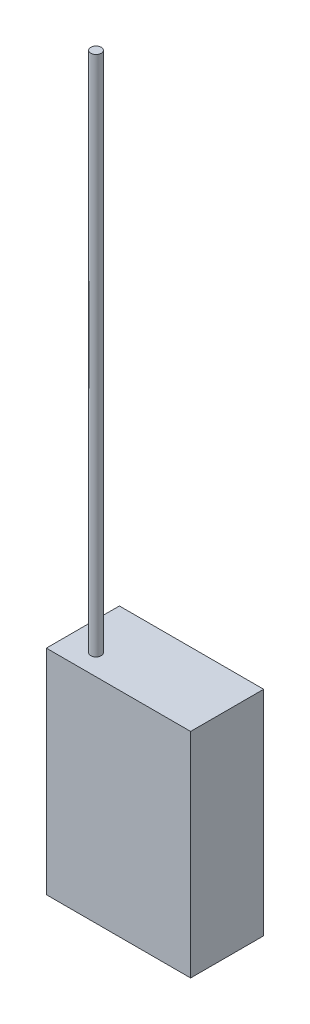
SolidWorks part; units mm, degrees
ref_plane "Front Plane" through (0, 0, 0) normal (0, 0, 1) x (1, 0, 0)
ref_plane "Top Plane" through (0, 0, 0) normal (0, 1, 0) x (1, 0, 0)
ref_plane "Right Plane" through (0, 0, 0) normal (1, 0, 0) x (0, 0, -1)
sketch "Sketch1" plane through (0, 0, 0) normal (0, 0, 1) x (1, 0, 0)
  line L1 (-63.0073, 12.0199) -> (-49.1804, 12.0199)
  line L2 (-63.0073, 12.0199) -> (-63.0073, -8.4439)
  line L3 (-63.0073, -8.4439) -> (-49.1804, -8.4439)
  line L4 (-49.1804, 12.0199) -> (-49.1804, -8.4439)
extrude "Boss-Extrude1" add sketch "Sketch1" along normal blind 7
sketch "Sketch2" plane through (0, 12.0199, 0) normal (0, 1, 0) x (1, 0, 0)
  line L0 (-85, 0) -> (85, 0) construction
  circle A0 centre (-60.2429, -5) radius 0.5
  dimension "D2" = 1
  dimension "D1" = 5
extrude "Boss-Extrude2" add sketch "Sketch2" along normal blind 50
